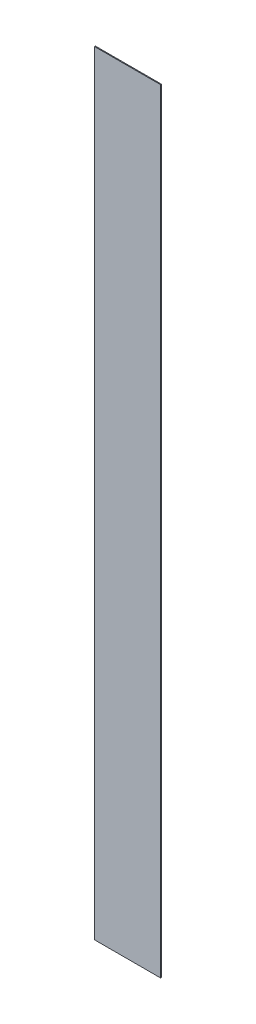
SolidWorks part; units mm, degrees
ref_plane "Front Plane" through (0, 0, 0) normal (0, 0, 1) x (1, 0, 0)
ref_plane "Top Plane" through (0, 0, 0) normal (0, 1, 0) x (1, 0, 0)
ref_plane "Right Plane" through (0, 0, 0) normal (1, 0, 0) x (0, 0, -1)
sketch "Sketch1" plane through (0, 0, 0) normal (0, 0, 1) x (1, 0, 0)
  line L0 (0, 0) -> (0, 1754)
  line L1 (0, 1754) -> (150, 1754)
  line L2 (150, 1754) -> (150, 0)
  line L3 (150, 0) -> (0, 0)
  dimension "D1" = 150
  dimension "D2" = 1754
extrude "Boss-Extrude1" add sketch "Sketch1" along normal blind 2
equation "\"Separator_panel_F_length\"=1750"
equation "\"D2@Sketch1\"= \"boxWidth\" - 88 - 88"
equation "\"CarBeamWidth\"=700.0"
equation "\"WheelWidth\"=650.0"
equation "\"Wheel_FrontBoxDistance\"=1390.0"
equation "\"boxLength\"=5100.0"
equation "\"boxWidth\"=1930.0"
equation "\"MetalSheet_3mm_length\"=5030.0"
equation "\"MetalSheet_3mm_width\"=1923.0"
equation "\"MetalSheet_3mm_FloorCut_L_length\"=1764.0"
equation "\"MetalSheet_3mm_FloorCut_L_disdance\"=1665.0"
equation "\"MetalSheet_3mm_FloorCut_R_length\"=1764.0"
equation "\"MetalSheet_3mm_FloorCut_R_disdance\"=1665.0"
equation "\"indoorHeight\"=1940.0"
equation "\"indoorHeight_para\"=25.0"
equation "\"rearLightHeight_para\"=265.0"
equation "\"doorColumnBar_A_FR_3mm_length_Cut\"=2310.0"
equation "\"A\"=0.0"
equation "\"haveDoor_R\"=1"
equation "\"side_door_bottom_R_3mm_length\"=1934.0"
equation "\"side_door_bottom_R_3mm_toFrontDistance\"=1583.0"
equation "\"1Bar_Side_RF_3mm_length\"=1493.0"
equation "\"1Bar_Side_RB_3mm_length\"=1493.0"
equation "\"DoorSeparator_RF_3mm_withHinge_toFrontDistance\"=1673.0"
equation "\"DoorSeparator_RF_3mm_withHinge_exist\"=1"
equation "\"DoorSeparator_RB_3mm_withHinge_toFrontDistance\"=3427.0"
equation "\"DoorSeparator_RB_3mm_withHinge_exist\"=1"
equation "\"Door_R1_L_open_Single_toFrontDistance\"=2547.5"
equation "\"Door_R1_L_open_Single_exist\"=1"
equation "\"door_base_long7_R1_L_open_Single_height\"=1890.0"
equation "\"door_base_short7_R1_L_open_Single_height\"=1890.0"
equation "\"door_base_short7_R1_L_open_Single_width\"=864"
equation "\"Door_R1_R_open_Single_toFrontDistance\"=3422.0"
equation "\"Door_R1_R_open_Single_exist\"=1"
equation "\"door_base_long7_R1_R_open_Single_height\"=1890.0"
equation "\"door_base_short7_R1_R_open_Single_height\"=1890.0"
equation "\"door_base_short7_R1_R_open_Single_width\"=864"
equation "\"x\"=66.0"
equation "\"door_base_double_BL_height\"=1890.0"
equation "\"door_base_short7_BL_Single_height\"=1890.0"
equation "\"door_base_short7_BL_Single_width\"=864"
equation "\"door_base_long7_BR_Single_height\"=1890.0"
equation "\"door_base_short7_BR_Single_height\"=1890.0"
equation "\"door_base_short7_BR_Single_width\"=864"
equation "\"da\"=62.0"
equation "\"SquareTube_length\"=1923.0"
equation "\"channelSteel_length\"=5030.0"
equation "\"SquareTube_inFront_AvgDistance\"=285.0"
equation "\"SquareTube_inFront_TotalCount\"=5"
equation "\"SquareTube_inFront1_cutDepth50_R\"=0.5"
equation "\"SquareTube_inFront1_cutDepth50_L\"=0.5"
equation "\"SquareTube_inFront2_cutDepth50_R\"=0.5"
equation "\"SquareTube_inFront2_cutDepth50_L\"=0.5"
equation "\"SquareTube_inFront3_cutDepth50_R\"=0.5"
equation "\"SquareTube_inFront3_cutDepth50_L\"=0.5"
equation "\"SquareTube_inFront4_cutDepth50_R\"=0.5"
equation "\"SquareTube_inFront4_cutDepth50_L\"=0.5"
equation "\"SquareTube_inFront5_cutDepth50_R\"=50"
equation "\"SquareTube_inFront5_cutDepth50_L\"=50"
equation "\"SquareTube_inFront6_cutDepth50_R\"=50"
equation "\"SquareTube_inFront6_cutDepth50_L\"=50"
equation "\"SquareTube_inFront7_cutDepth50_R\"=50"
equation "\"SquareTube_inFront7_cutDepth50_L\"=50"
equation "\"SquareTube_inFront8_cutDepth50_R\"=50"
equation "\"SquareTube_inFront8_cutDepth50_L\"=50"
equation "\"SquareTube_inFront9_cutDepth50_R\"=50"
equation "\"SquareTube_inFront9_cutDepth50_L\"=50"
equation "\"SquareTube_inFront10_cutDepth50_R\"=50"
equation "\"SquareTube_inFront10_cutDepth50_L\"=50"
equation "\"SquareTube_inFront11_cutDepth50_R\"=50"
equation "\"SquareTube_inFront11_cutDepth50_L\"=50"
equation "\"SquareTube_inFront12_cutDepth50_R\"=50"
equation "\"SquareTube_inFront12_cutDepth50_L\"=50"
equation "\"SquareTube_inFront13_cutDepth50_R\"=50"
equation "\"SquareTube_inFront13_cutDepth50_L\"=50"
equation "\"SquareTube_inFront14_cutDepth50_R\"=50"
equation "\"SquareTube_inFront14_cutDepth50_L\"=50"
equation "\"SquareTube_inBack_AvgDistance\"=333.125"
equation "\"SquareTube_inBack_TotalCount\"=9"
equation "\"SquareTube_inBack1_cutDepth50_R\"=50"
equation "\"SquareTube_inBack1_cutDepth50_L\"=50"
equation "\"SquareTube_inBack2_cutDepth50_R\"=50"
equation "\"SquareTube_inBack2_cutDepth50_L\"=50"
equation "\"SquareTube_inBack3_cutDepth50_R\"=50"
equation "\"SquareTube_inBack3_cutDepth50_L\"=50"
equation "\"SquareTube_inBack4_cutDepth50_R\"=50"
equation "\"SquareTube_inBack4_cutDepth50_L\"=50"
equation "\"SquareTube_inBack5_cutDepth50_R\"=50"
equation "\"SquareTube_inBack5_cutDepth50_L\"=50"
equation "\"SquareTube_inBack6_cutDepth50_R\"=0.5"
equation "\"SquareTube_inBack6_cutDepth50_L\"=0.5"
equation "\"SquareTube_inBack7_cutDepth50_R\"=0.5"
equation "\"SquareTube_inBack7_cutDepth50_L\"=0.5"
equation "\"SquareTube_inBack8_cutDepth50_R\"=0.5"
equation "\"SquareTube_inBack8_cutDepth50_L\"=0.5"
